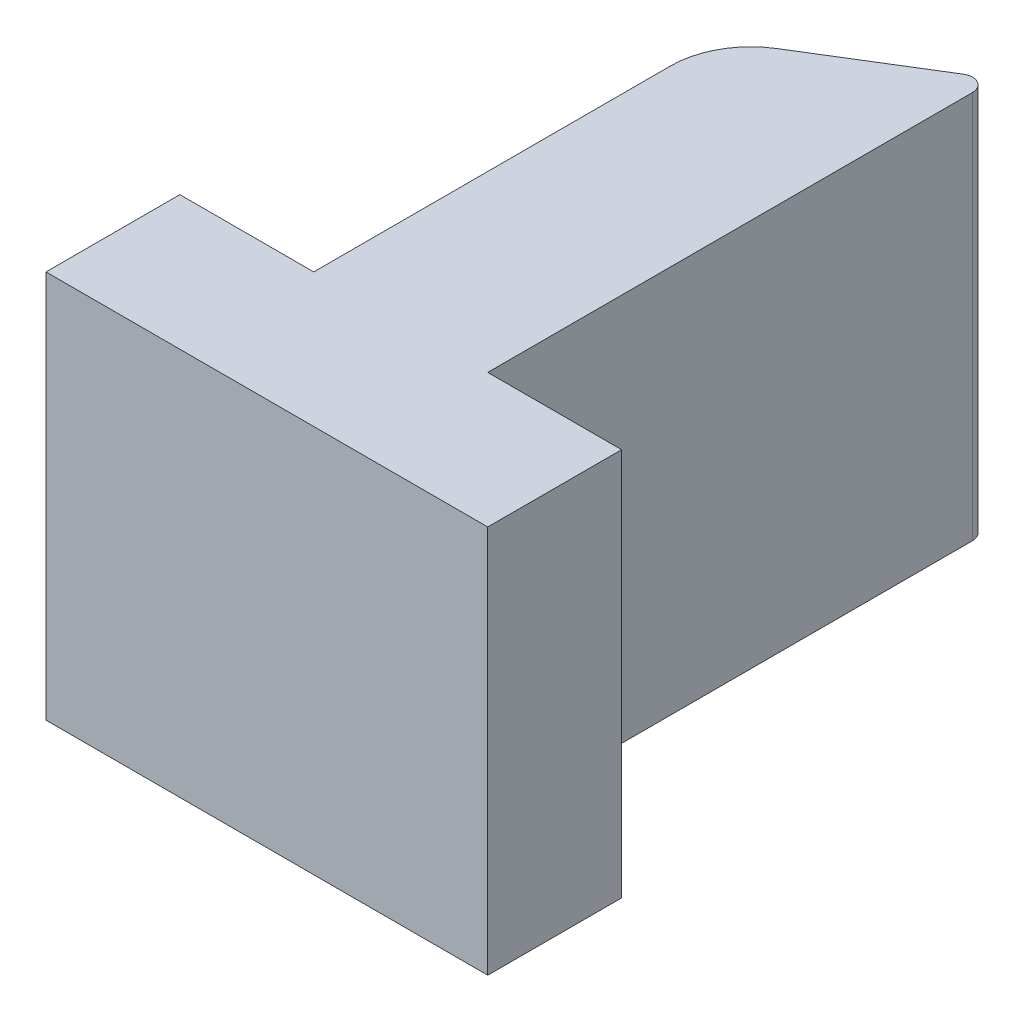
SolidWorks part; units mm, degrees
material "POM 乙缩醛共聚物"
ref_plane "前视基准面" through (0, 0, 0) normal (0, 0, 1) x (1, 0, 0)
ref_plane "上视基准面" through (0, 0, 0) normal (0, 1, 0) x (1, 0, 0)
ref_plane "右视基准面" through (0, 0, 0) normal (1, 0, 0) x (0, 0, -1)
sketch "草图1" plane through (0, 0, 0) normal (0, 1, 0) x (1, 0, 0)
  line L0 (0, 0) -> (6.5, 4)
  line L1 (6.5, 4) -> (6.5, -15)
  line L2 (6.5, -15) -> (11.5, -15)
  line L3 (11.5, -15) -> (11.5, -20)
  line L4 (11.5, -20) -> (-5, -20)
  line L5 (-5, -20) -> (-5, -15)
  line L6 (-5, -15) -> (0, -15)
  line L7 (0, -15) -> (0, 0)
  dimension "D1" = 16.5
  dimension "D2" = 15
  dimension "D3" = 19
  dimension "D4" = 4
  dimension "D5" = 5
  dimension "D6" = 5
  dimension "D7" = 5
extrude "凸台-拉伸1" add sketch "草图1" along normal blind 14.5
fillet "圆角1" radius 3 1 edges at (0, 7.25, 0)
fillet "圆角2" radius 0.5 1 edges at (6.5, 7.25, -4)
